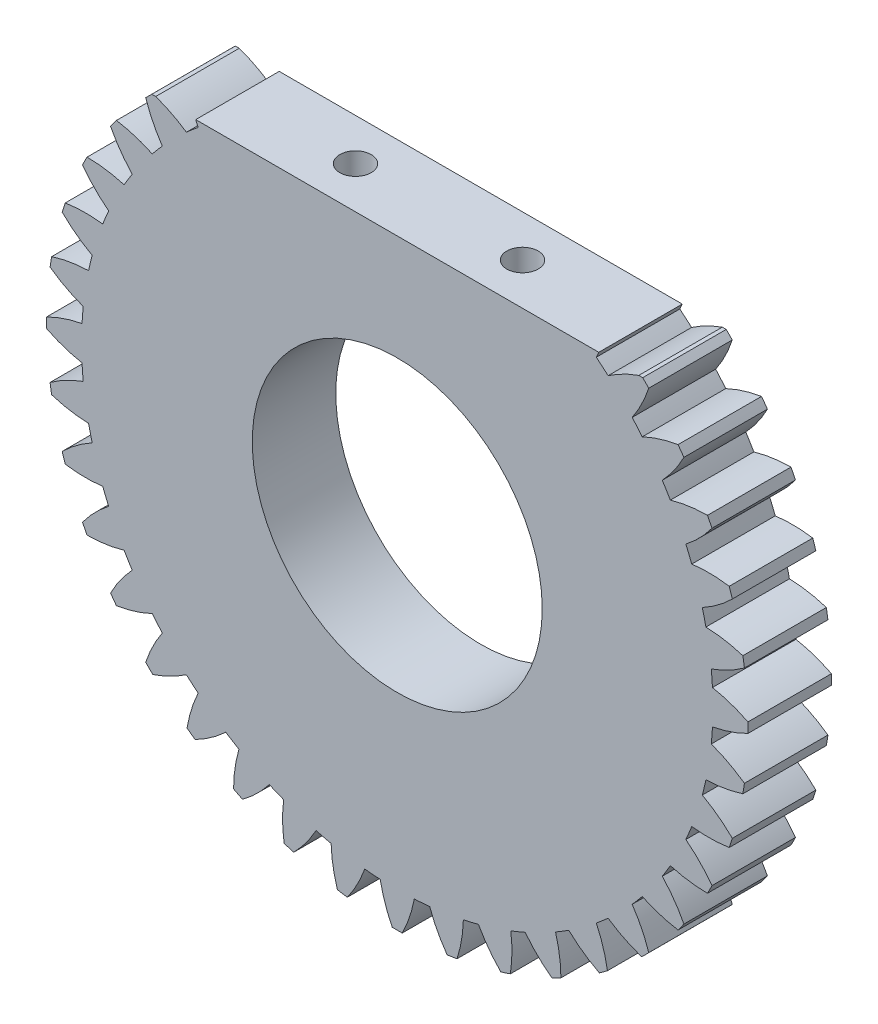
SolidWorks part; units mm, degrees
ref_plane "Front Plane" through (0, 0, 0) normal (0, 0, 1) x (1, 0, 0)
ref_plane "Top Plane" through (0, 0, 0) normal (0, 1, 0) x (1, 0, 0)
ref_plane "Right Plane" through (0, 0, 0) normal (1, 0, 0) x (0, 0, -1)
sketch "Sketch1" plane through (0, 0, 0) normal (0, 0, 1) x (1, 0, 0)
  circle A0 centre (0, 0) radius 24.003
  dimension "D1" = 48.006
extrude "Boss-Extrude1" add sketch "Sketch1" against normal mid plane 6.35
sketch "Sketch2" plane through (0, 0, 3.175) normal (0, 0, 1) x (1, 0, 0)
  line L0 (0, 29.2308) -> (0, 0) construction
  arc A8 (-1.2954, 23.968) -> (-0.381, 26.6673) centre (8.6895, 22.09) cw
  arc A9 (1.2954, 23.968) -> (0.381, 26.6673) centre (-8.6895, 22.09) ccw
  arc A14 (0.381, 26.6673) -> (-0.381, 26.6673) centre (0, 0) ccw
  arc A15 (1.2954, 23.968) -> (-1.2954, 23.968) centre (0, 0) ccw
  dimension "D2" = 53.34
  dimension "D3" = 48.006
  dimension "D9" = 10.16
  dimension "D11" = 0.762
  dimension "D10" = 2.5908
extrude "Boss-Extrude2" add sketch "Sketch2" against normal up to surface (6.35 mm away) up to face at (24.003, 0, -3.175)
pattern_circular "CirPattern2" count 40 over 360 about axis through (0, 0, 0) along (0, 0, 1) of "Boss-Extrude2"
sketch "Sketch3" plane through (0, 0, 3.175) normal (0, 0, 1) x (1, 0, 0)
  line L1 (-25.4, 31.75) -> (25.4, 31.75)
  line L2 (-25.4, 31.75) -> (-25.4, 19.05)
  line L3 (-25.4, 19.05) -> (25.4, 19.05)
  line L4 (25.4, 31.75) -> (25.4, 19.05)
  point P4 (0, 19.05)
  dimension "D1" = 19.05
  dimension "D2" = 12.7
  dimension "D3" = 50.8
extrude "Cut-Extrude1" cut sketch "Sketch3" against normal through all
sketch "Sketch6" plane through (0, 0, 3.175) normal (0, 0, 1) x (1, 0, 0)
  circle A0 centre (0, 0) radius 11.025
  dimension "D1" = 22.05
extrude "Cut-Extrude4" cut sketch "Sketch6" against normal through all
sketch "Sketch7" plane through (0, 19.05, 0) normal (0, 1, 0) x (1, 0, 0)
  line L0 (-6.35, 0) -> (6.35, 0) construction
  circle A0 centre (-6.35, 0) radius 1.1938
  circle A1 centre (6.35, 0) radius 1.1938
  point P3 (0, 0)
  dimension "D1" = 2.3876
  dimension "D2" = 12.7
extrude "Cut-Extrude5" cut sketch "Sketch7" against normal blind 7.8232 and the other way through all
